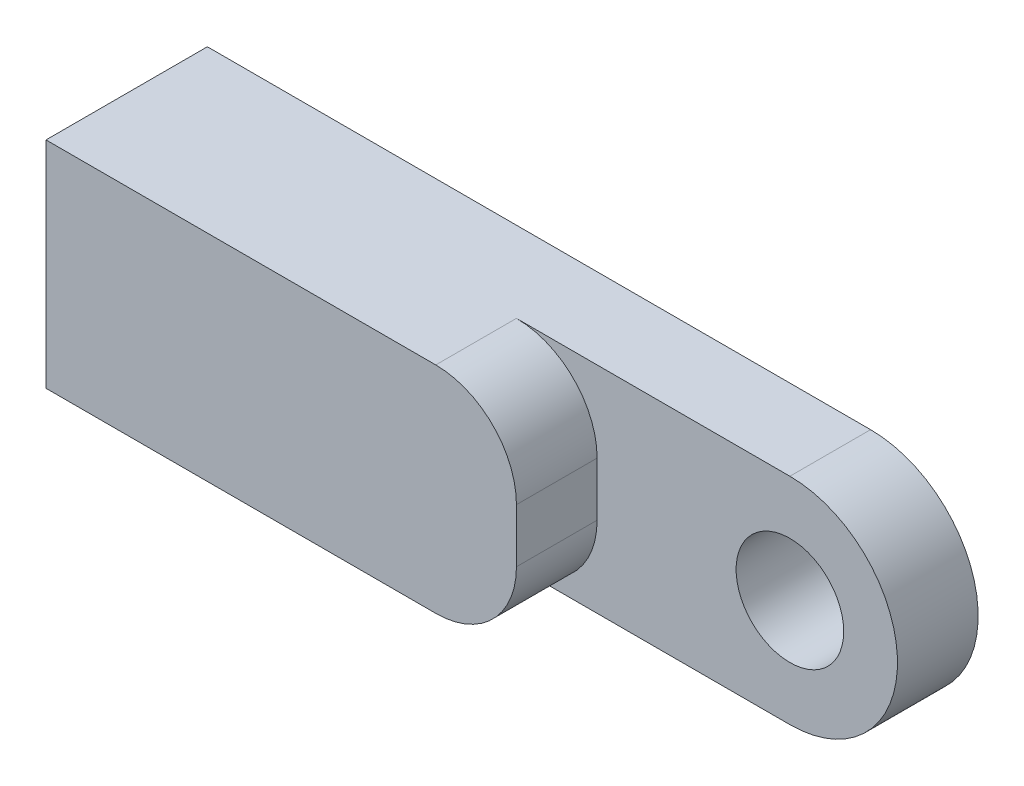
SolidWorks part; units mm, degrees
ref_plane "Front Plane" through (0, 0, 0) normal (0, 0, 1) x (1, 0, 0)
ref_plane "Top Plane" through (0, 0, 0) normal (0, 1, 0) x (1, 0, 0)
ref_plane "Right Plane" through (0, 0, 0) normal (1, 0, 0) x (0, 0, -1)
sketch "Sketch1" plane through (0, 0, 0) normal (0, 0, 1) x (1, 0, 0)
  line L0 (-150, 0) -> (0, 0) construction
  line L1 (0, 0) -> (125, 0) construction
  line L2 (-150, 40) -> (125, 40)
  line L3 (-150, -40) -> (125, -40)
  circle A0 centre (-150, 0) radius 20
  circle A1 centre (125, 0) radius 20
  arc A2 (-150, 40) -> (-150, -40) centre (-150, 0) ccw
  arc A3 (125, -40) -> (125, 40) centre (125, 0) ccw
  dimension "D3" = 40
  dimension "D4" = 40
  dimension "D5" = 80
  dimension "D6" = 80
  dimension "D1" = 150
  dimension "D2" = 125
extrude "Boss-Extrude1" add sketch "Sketch1" along normal blind 60
sketch "Sketch2" plane through (0, 0, 60) normal (0, 0, 1) x (1, 0, 0)
  circle A0 centre (125, 0) radius 45
  dimension "D1" = 90
extrude "Cut-Extrude1" cut sketch "Sketch2" against normal blind 30 contours A0
sketch "Sketch3" plane through (0, -40, 0) normal (0, -1, 0) x (1, 0, 0)
  line L0 (-150, 60) -> (-210.1729, 60)
  line L1 (-210.1729, 60) -> (-210.1729, 0)
  line L4 (-150, 60) -> (104.3845, 60) construction
  line L5 (-130, 60) -> (-170, 60) construction
  line L6 (-130, 60) -> (-150, 60)
  line L7 (-210.1729, 0) -> (-121.612, 0)
  line L8 (-150, 0) -> (125, 0) construction
  line L9 (-121.612, 0) -> (-121.612, 60)
  line L10 (-121.612, 60) -> (-130, 60)
extrude "Cut-Extrude2" cut sketch "Sketch3" against normal blind 131
sketch "Sketch4" plane through (-121.612, 0, 0) normal (-1, 0, 0) x (0, 0, 1)
  line L0 (0, 40) -> (60, -40) construction
  circle A0 centre (30, 0) radius 7.5
  dimension "D1" = 15
extrude "Cut-Extrude3" cut sketch "Sketch4" against normal blind 10
sketch "Sketch5" plane through (0, 0, 60) normal (0, 0, 1) x (1, 0, 0)
  line L1 (104.3845, -40) -> (125, -40) construction
  line L2 (107.0576, -40) -> (53.3156, -40)
  line L3 (-121.612, -40) -> (104.3845, -40) construction
  line L4 (53.3156, -40) -> (53.3156, 40)
  line L5 (104.3845, 40) -> (-121.612, 40) construction
  line L7 (53.3156, 40) -> (107.0576, 40)
  line L8 (125, 40) -> (104.3845, 40) construction
  line L9 (107.0576, 40) -> (107.0576, -40)
extrude "Cut-Extrude7" cut sketch "Sketch5" against normal blind 30
fillet "Fillet1" radius 30 2 edges at (53.3156, 40, 45) (53.3156, -40, 45)
